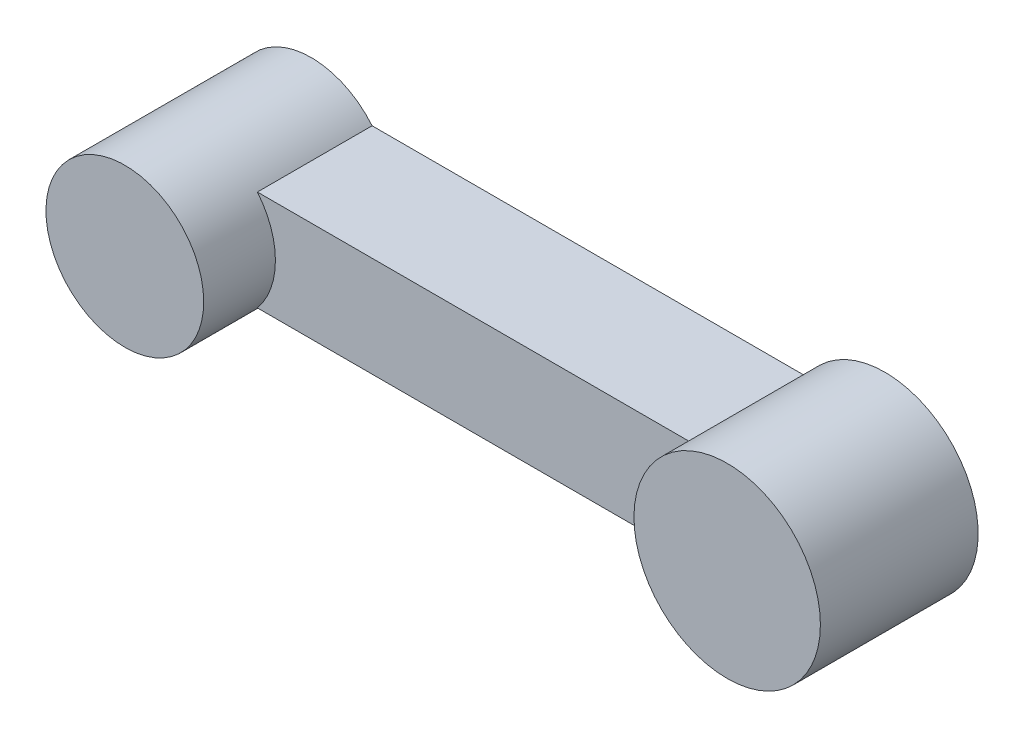
SolidWorks part; units mm, degrees
ref_plane "Front Plane" through (0, 0, 0) normal (0, 0, 1) x (1, 0, 0)
ref_plane "Top Plane" through (0, 0, 0) normal (0, 1, 0) x (1, 0, 0)
ref_plane "Right Plane" through (0, 0, 0) normal (1, 0, 0) x (0, 0, -1)
sketch "草图3" plane through (0, 0, 0) normal (0, 0, 1) x (1, 0, 0)
  line L0 (20, 5) -> (100, 5)
  line L1 (100, 5) -> (100, 19)
  line L2 (100, 19) -> (20, 19)
  line L3 (20, 19) -> (20, 5)
  dimension "x0" = 20
  dimension "x1" = 100
  dimension "y0" = 5
  dimension "y2" = 19
extrude "Bar" add sketch "草图3" along normal blind 16
sketch "草图4" plane through (0, 0, 0) normal (0, 0, 1) x (1, 0, 0)
  circle A0 centre (20, 12) radius 11
  dimension "diameter" = 22
  dimension "x" = 20
  dimension "y" = 12
extrude "RootHub" add sketch "草图4" along normal blind 26
sketch "草图5" plane through (0, 0, 0) normal (0, 0, 1) x (1, 0, 0)
  circle A0 centre (100, 12) radius 13
  dimension "diameter" = 26
  dimension "x" = 100
  dimension "y" = 12
extrude "EndHub" add sketch "草图5" along normal blind 22
